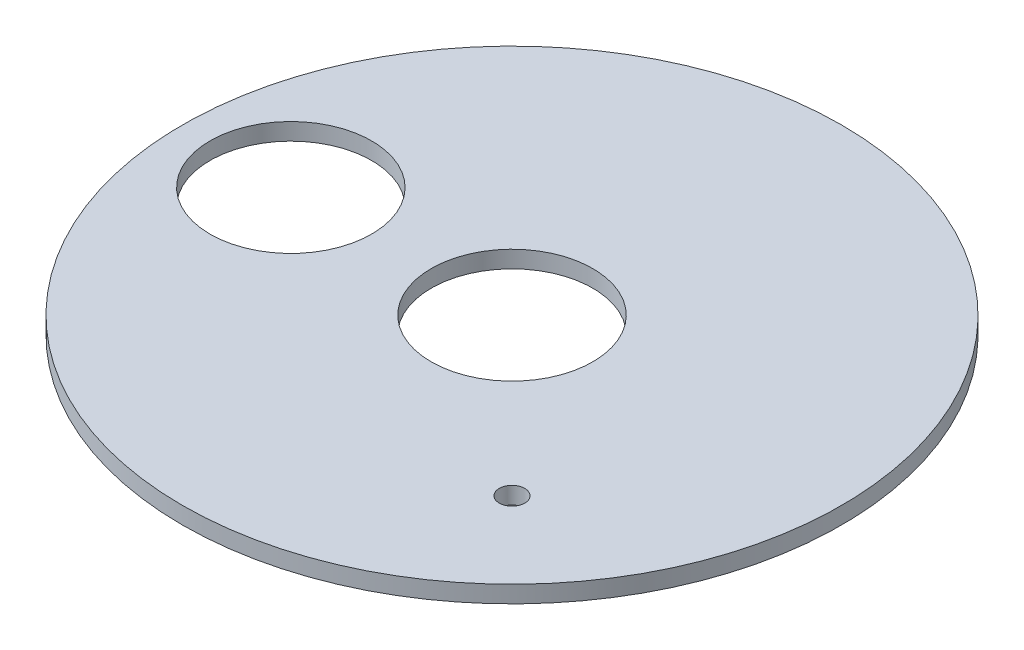
SolidWorks part; units mm, degrees
material "Oak"
ref_plane "Front Plane" through (0, 0, 0) normal (0, 0, 1) x (1, 0, 0)
ref_plane "Top Plane" through (0, 0, 0) normal (0, 1, 0) x (1, 0, 0)
ref_plane "Right Plane" through (0, 0, 0) normal (1, 0, 0) x (0, 0, -1)
sketch "Sketch1" plane through (0, 0, 0) normal (0, 1, 0) x (1, 0, 0)
  circle A0 centre (0, 0) radius 123
  dimension "D1" = 246
extrude "Boss-Extrude1" add sketch "Sketch1" along normal blind 6.35
sketch "Sketch2" plane through (0, 6.35, 0) normal (0, 1, 0) x (1, 0, 0)
  line L0 (0, 0) -> (-82.55, 0) construction
  circle A0 centre (0, 0) radius 30.1625
  circle A1 centre (-82.55, 0) radius 30.1625
  dimension "D1" = 60.325
  dimension "D2" = 82.55
extrude "Cut-Extrude1" cut sketch "Sketch2" against normal through all
sketch "Sketch3" plane through (0, 6.35, 0) normal (0, 1, 0) x (1, 0, 0)
  line L0 (0, 0) -> (86.9741, -86.9741) construction
  line L1 (0, 0) -> (0, 123) construction
  circle A0 centre (0, 0) radius 123 construction
  circle A1 centre (58.3717, -58.3717) radius 4.7625
  dimension "D1" = 9.525
  dimension "D3" = 82.55
  dimension "D2" = 135
extrude "Cut-Extrude2" cut sketch "Sketch3" against normal up to next
